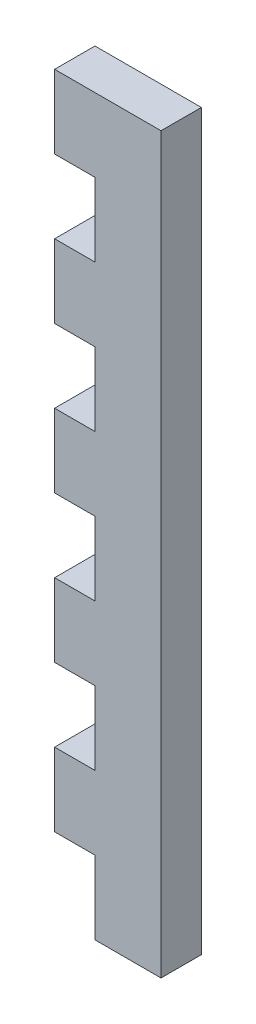
SolidWorks part; units mm, degrees
material "ﾁｰｸ材"
ref_plane "正面" through (0, 0, 0) normal (0, 0, 1) x (1, 0, 0)
ref_plane "平面" through (0, 0, 0) normal (0, 1, 0) x (1, 0, 0)
ref_plane "右側面" through (0, 0, 0) normal (1, 0, 0) x (0, 0, -1)
sketch "ｽｹｯﾁ1" plane through (0, 0, 0) normal (0, 0, 1) x (1, 0, 0)
  line L1 (0, 0) -> (14.5, 0)
  line L2 (0, 0) -> (0, -100)
  line L3 (0, -100) -> (14.5, -100)
  line L4 (14.5, 0) -> (14.5, -100)
  dimension "D1" = 14.5
  dimension "D2" = 100
extrude "ﾎﾞｽ - 押し出し1" add sketch "ｽｹｯﾁ1" along normal blind 5.5
sketch "ｽｹｯﾁ2" plane through (0, 0, 5.5) normal (0, 0, 1) x (1, 0, 0)
  line L0 (0, 0) -> (0, -100) construction
  line L1 (0, -20) -> (5.5, -20)
  line L2 (0, -20) -> (0, -10)
  line L3 (0, -10) -> (5.5, -10)
  line L4 (5.5, -20) -> (5.5, -10)
  line L5 (0, -40) -> (0, -30)
  line L6 (14.5, 0) -> (0, 0) construction
  line L7 (0, -40) -> (5.5, -40)
  line L8 (5.5, -40) -> (5.5, -30)
  line L9 (0, -30) -> (5.5, -30)
  line L10 (0, -60) -> (0, -50)
  line L11 (0, -60) -> (5.5, -60)
  line L12 (5.5, -60) -> (5.5, -50)
  line L13 (0, -50) -> (5.5, -50)
  line L14 (0, -80) -> (0, -70)
  line L15 (0, -80) -> (5.5, -80)
  line L16 (5.5, -80) -> (5.5, -70)
  line L17 (0, -70) -> (5.5, -70)
  line L18 (0, -100) -> (0, -90)
  line L19 (0, -100) -> (5.5, -100)
  line L20 (5.5, -100) -> (5.5, -90)
  line L21 (0, -90) -> (5.5, -90)
  dimension "D1" = 10
  dimension "D2" = 10
  dimension "D4" = 5.5
  dimension "D3" = 5
extrude "ｶｯﾄ - 押し出し1" cut sketch "ｽｹｯﾁ2" against normal through all
